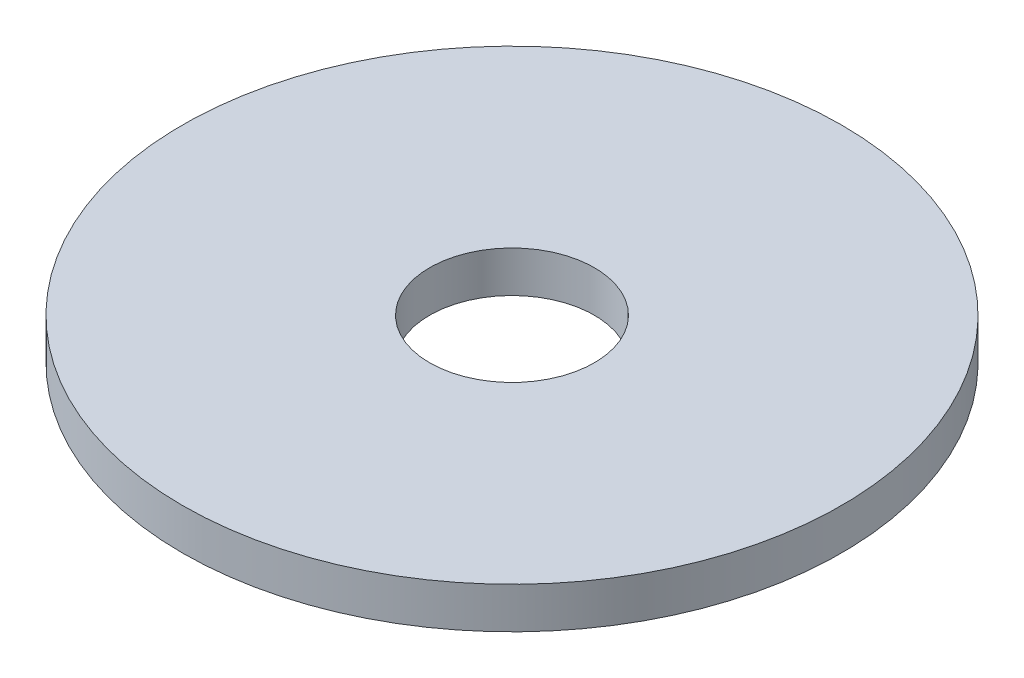
SolidWorks part; units mm, degrees
material "AISI 304"
ref_plane "前视基准面" through (0, 0, 0) normal (0, 0, 1) x (1, 0, 0)
ref_plane "上视基准面" through (0, 0, 0) normal (0, 1, 0) x (1, 0, 0)
ref_plane "右视基准面" through (0, 0, 0) normal (1, 0, 0) x (0, 0, -1)
other "Configuration Table"
sketch "草图1" plane through (0, 0, 0) normal (0, 1, 0) x (1, 0, 0)
  circle A0 centre (0, 0) radius 1
  circle A1 centre (0, 0) radius 4
  dimension "D1" = 2
  dimension "D2" = 8
extrude "凸台-拉伸1" add sketch "草图1" along normal blind 0.5
